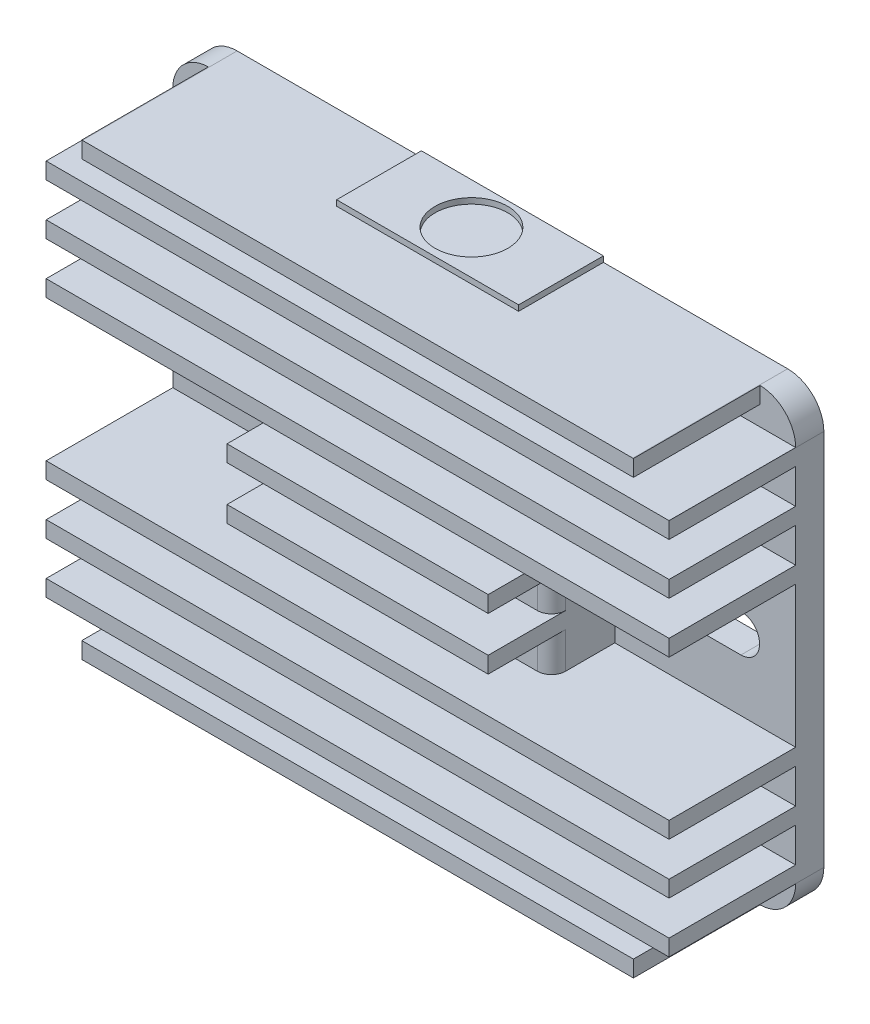
SolidWorks part; units mm, degrees
ref_plane "正面" through (0, 0, 0) normal (0, 0, 1) x (1, 0, 0)
ref_plane "平面" through (0, 0, 0) normal (0, 1, 0) x (1, 0, 0)
ref_plane "右側面" through (0, 0, 0) normal (1, 0, 0) x (0, 0, -1)
sketch "ｽｹｯﾁ1" plane through (0, 0, 0) normal (0, 0, 1) x (1, 0, 0)
  line L1 (0, 0) -> (110.2, 0)
  line L2 (0, 0) -> (0, 79.6)
  line L3 (0, 79.6) -> (110.2, 79.6)
  line L4 (110.2, 0) -> (110.2, 79.6)
  dimension "D1" = 79.6
  dimension "D2" = 110.2
extrude "ﾎﾞｽ - 押し出し1" add sketch "ｽｹｯﾁ1" along normal blind 4.99
sketch "ｽｹｯﾁ2" plane through (0, 0, 4.99) normal (0, 0, 1) x (1, 0, 0)
  line L0 (29, 79.6) -> (29, 73.2)
  line L1 (110.2, 79.6) -> (0, 79.6) construction
  line L2 (29, 73.2) -> (81.2, 73.2)
  line L3 (81.2, 73.2) -> (81.2, 79.6)
  line L4 (81.2, 79.6) -> (29, 79.6)
  line L5 (110.2, 0) -> (110.2, 79.6) construction
  line L6 (0, 79.6) -> (0, 0) construction
  dimension "D1" = 29
  dimension "D2" = 29
  dimension "D3" = 6.4
extrude "ﾎﾞｽ - 押し出し2" add sketch "ｽｹｯﾁ2" along normal blind 15
sketch "ｽｹｯﾁ3" plane through (0, 0, 4.99) normal (0, 0, 1) x (1, 0, 0)
  line L0 (32, 73.2) -> (32, 0)
  line L1 (29, 73.2) -> (81.2, 73.2) construction
  line L2 (0, 0) -> (110.2, 0) construction
  line L3 (32, 0) -> (78.2, 0)
  line L4 (78.2, 0) -> (78.2, 73.2)
  line L5 (78.2, 73.2) -> (32, 73.2)
  line L6 (0, 79.6) -> (0, 0) construction
  line L7 (110.2, 0) -> (110.2, 79.6) construction
  dimension "D1" = 32
  dimension "D2" = 32
extrude "ﾎﾞｽ - 押し出し3" add sketch "ｽｹｯﾁ3" along normal blind 11.2
sketch "ｽｹｯﾁ4" plane through (0, 0, 4.99) normal (0, 0, 1) x (1, 0, 0)
  line L0 (0, 39.8) -> (110.2, 39.8) construction
  line L1 (0, 79.6) -> (0, 0) construction
  line L2 (110.2, 0) -> (110.2, 79.6) construction
  line L3 (55.1, 79.6) -> (55.1, 0) construction
  line L4 (81.2, 79.6) -> (29, 79.6) construction
  line L5 (32, 0) -> (78.2, 0) construction
  line L6 (103.9, 79.6) -> (6.3, 79.6)
  line L7 (29, 79.6) -> (0, 79.6) construction
  line L8 (6.3, 79.6) -> (6.3, 76.7)
  line L9 (6.3, 76.7) -> (103.9, 76.7)
  line L10 (103.9, 79.6) -> (103.9, 76.7)
  line L11 (6.3, 2.9) -> (103.9, 2.9)
  line L12 (103.9, 0) -> (103.9, 2.9)
  line L13 (103.9, 0) -> (6.3, 0)
  line L14 (6.3, 0) -> (6.3, 2.9)
  line L15 (78.2, 43) -> (32, 43)
  line L16 (32, 73.2) -> (32, 0) construction
  line L17 (32, 43) -> (32, 45.9)
  line L18 (32, 73.2) -> (32, 0) construction
  line L19 (32, 45.9) -> (78.2, 45.9)
  line L20 (78.2, 43) -> (78.2, 45.9)
  line L21 (78.2, 36.6) -> (78.2, 33.7)
  line L22 (78.2, 36.6) -> (32, 36.6)
  line L23 (32, 36.6) -> (32, 33.7)
  line L24 (32, 33.7) -> (78.2, 33.7)
  line L25 (110.2, 52.3) -> (0, 52.3)
  line L26 (0, 52.3) -> (0, 55.2)
  line L27 (0, 55.2) -> (110.2, 55.2)
  line L28 (110.2, 52.3) -> (110.2, 55.2)
  line L29 (110.2, 27.3) -> (110.2, 24.4)
  line L30 (110.2, 27.3) -> (0, 27.3)
  line L31 (0, 27.3) -> (0, 24.4)
  line L32 (0, 24.4) -> (110.2, 24.4)
  line L33 (110.2, 73.2319) -> (0, 73.2319)
  line L34 (0, 73.2319) -> (0, 70.3319)
  line L35 (0, 70.3319) -> (110.2, 70.3319)
  line L36 (110.2, 73.2319) -> (110.2, 70.3319)
  line L37 (110.2, 6.3681) -> (110.2, 9.2681)
  line L38 (0, 9.2681) -> (110.2, 9.2681)
  line L39 (0, 6.3681) -> (0, 9.2681)
  line L40 (110.2, 6.3681) -> (0, 6.3681)
  line L41 (110.2, 18.2841) -> (110.2, 15.3841)
  line L42 (0, 18.2841) -> (110.2, 18.2841)
  line L43 (0, 61.3159) -> (0, 64.2159)
  line L44 (0, 64.2159) -> (110.2, 64.2159)
  line L45 (0, 61.3159) -> (110.2, 61.3159)
  line L46 (110.2, 61.3159) -> (110.2, 64.2159)
  line L47 (0, 18.2841) -> (0, 15.3841)
  line L48 (0, 15.3841) -> (110.2, 15.3841)
  point P18 (55.1, 76.7)
  point P31 (55.1, 43)
  point P33 (55.1, 45.9)
  point P42 (55.1, 52.3)
  point P43 (55.1, 55.2)
  point P47 (55.1, 70.3319)
  point P53 (55.1, 73.2319)
  point P66 (55.1, 61.3159)
  point P67 (55.1, 64.2159)
  dimension "D1" = 48.8
  dimension "D2" = 2.9
  dimension "D3" = 3.2
  dimension "D4" = 2.9
  dimension "D5" = 6.4
  dimension "D6" = 2.9
  dimension "D7" = 2.9
extrude "ﾎﾞｽ - 押し出し4" add sketch "ｽｹｯﾁ4" along normal blind 22.4
sketch "ｽｹｯﾁ5" plane through (0, 0, 4.99) normal (0, 0, 1) x (1, 0, 0)
  line L0 (0, 52.3) -> (110.2, 52.3) construction
  line L1 (6.3866, 43.3) -> (23.7262, 43.3)
  line L2 (6.3866, 43.3) -> (6.3866, 36.6)
  line L3 (6.3866, 36.6) -> (23.7262, 36.6)
  line L4 (23.7262, 43.3) -> (23.7262, 36.6)
  line L5 (55.1, 79.6) -> (55.1, 0) construction
  line L6 (103.9, 79.6) -> (6.3, 79.6) construction
  line L7 (6.3, 0) -> (103.9, 0) construction
  line L8 (86.4738, 43.3) -> (86.4738, 36.6)
  line L9 (103.8134, 36.6) -> (86.4738, 36.6)
  line L10 (103.8134, 43.3) -> (103.8134, 36.6)
  line L11 (103.8134, 43.3) -> (86.4738, 43.3)
  dimension "D1" = 9
  dimension "D2" = 6.7
extrude "ｶｯﾄ - 押し出し1" cut sketch "ｽｹｯﾁ5" against normal through all
fillet "ﾌｨﾚｯﾄ1" radius 3.3 8 edges at (103.8134, 36.6, 2.495) (86.4738, 36.6, 2.495) (86.4738, 43.3, 2.495) (103.8134, 43.3, 2.495) (23.7262, 36.6, 2.495) (6.3866, 36.6, 2.495) (23.7262, 43.3, 2.495) (6.3866, 43.3, 2.495)
fillet "ﾌｨﾚｯﾄ2" radius 6.4 4 edges at (0, 0, 2.495) (110.2, 0, 2.495) (110.2, 79.6, 2.495) (0, 79.6, 2.495)
fillet "ﾌｨﾚｯﾄ3" radius 2.5 18 edges at (81.2, 74.9659, 19.99) (78.2, 67.2739, 16.19) (78.2, 58.258, 16.19) (78.2, 49.1, 16.19) (78.2, 39.8, 16.19) (78.2, 30.5, 16.19) (78.2, 21.342, 16.19) (78.2, 12.3261, 16.19) (78.2, 4.6341, 16.19) (32, 4.6341, 16.19) (32, 12.3261, 16.19) (32, 21.342, 16.19) (32, 30.5, 16.19) (32, 39.8, 16.19) (32, 49.1, 16.19) (32, 58.258, 16.19) (32, 67.2739, 16.19) (29, 74.9659, 19.99)
sketch "ｽｹｯﾁ6" plane through (0, 79.6, 0) normal (0, 1, 0) x (1, 0, 0)
  line L0 (55.1, 0) -> (55.1, -27.39) construction
  line L1 (103.8, 0) -> (6.4, 0) construction
  line L2 (103.8, -27.39) -> (6.4, -27.39) construction
  line L3 (71.2, 0) -> (39, 0)
  line L4 (39, 0) -> (39, -15)
  line L5 (39, -15) -> (71.2, -15)
  line L6 (71.2, 0) -> (71.2, -15)
  point P11 (55.1, -15)
  dimension "D1" = 16.1
  dimension "D2" = 15
extrude "ﾎﾞｽ - 押し出し5" add sketch "ｽｹｯﾁ6" along normal blind 1
sketch "ｽｹｯﾁ7" plane through (0, 80.6, 0) normal (0, 1, 0) x (1, 0, 0)
  circle A0 centre (55.1542, -7.301) radius 6.4388
extrude "ｶｯﾄ - 押し出し2" cut sketch "ｽｹｯﾁ7" against normal blind 1
